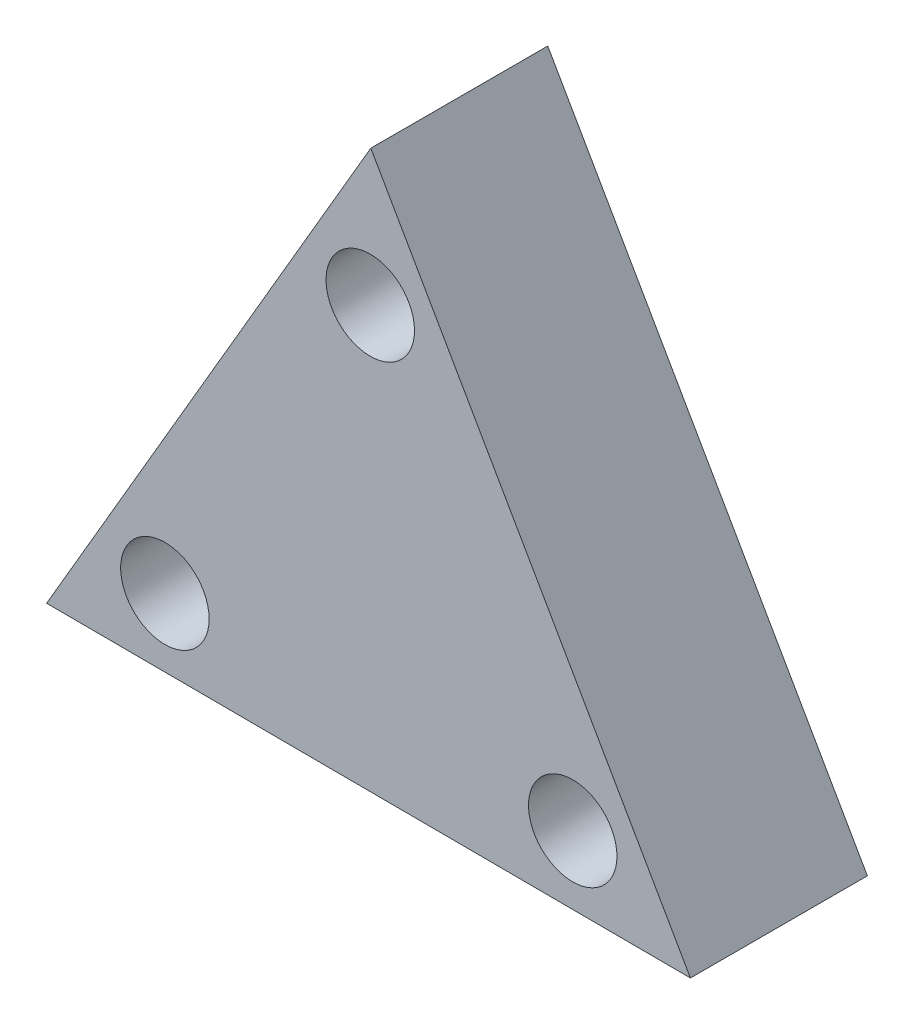
SolidWorks part; units mm, degrees
ref_plane "Plan de face" through (0, 0, 0) normal (0, 0, 1) x (1, 0, 0)
ref_plane "Plan de dessus" through (0, 0, 0) normal (0, 1, 0) x (1, 0, 0)
ref_plane "Plan de droite" through (0, 0, 0) normal (1, 0, 0) x (0, 0, -1)
sketch "Esquisse13" plane through (0, 0, 0) normal (0, 0, 1) x (1, 0, 0)
  line L1 (0.0446, 12.6118) -> (-10.9481, -6.2485)
  line L2 (-10.9481, -6.2485) -> (10.8817, -6.3383)
  line L3 (10.8817, -6.3383) -> (0.0446, 12.6118)
  circle A0 centre (-0.0073, 0.0083) radius 6.3018 construction
  dimension "D1" = 21.83
extrude "Boss.-Extru.1" add sketch "Esquisse13" along normal blind 6
sketch "Esquisse14" plane through (0, 0, 6) normal (0, 0, 1) x (1, 0, 0)
  line L0 (-10.9481, -6.2485) -> (10.8817, -6.3383) construction
  line L1 (0.0256, 7.9918) -> (-6.9376, -3.955)
  line L2 (-6.9376, -3.955) -> (6.8902, -4.0119)
  line L3 (6.8902, -4.0119) -> (0.0256, 7.9918)
  line L4 (10.8817, -6.3383) -> (0.0446, 12.6118) construction
  line L5 (0.0446, 12.6118) -> (-10.9481, -6.2485) construction
  circle A0 centre (-0.0073, 0.0083) radius 3.9918 construction
  circle A1 centre (0.0258, 7.9912) radius 1.5
  circle A2 centre (6.891, -4.0104) radius 1.5
  circle A3 centre (-6.9378, -3.955) radius 1.5
  dimension "D4" = 3
  dimension "D5" = 3
  dimension "D6" = 3
  dimension "D1" = 2.31
  dimension "D2" = 2.31
  dimension "D3" = 2.31
extrude "Enlèv. mat.-Extru.1" cut sketch "Esquisse14" against normal blind 8 contours A1 | A2 | A3
